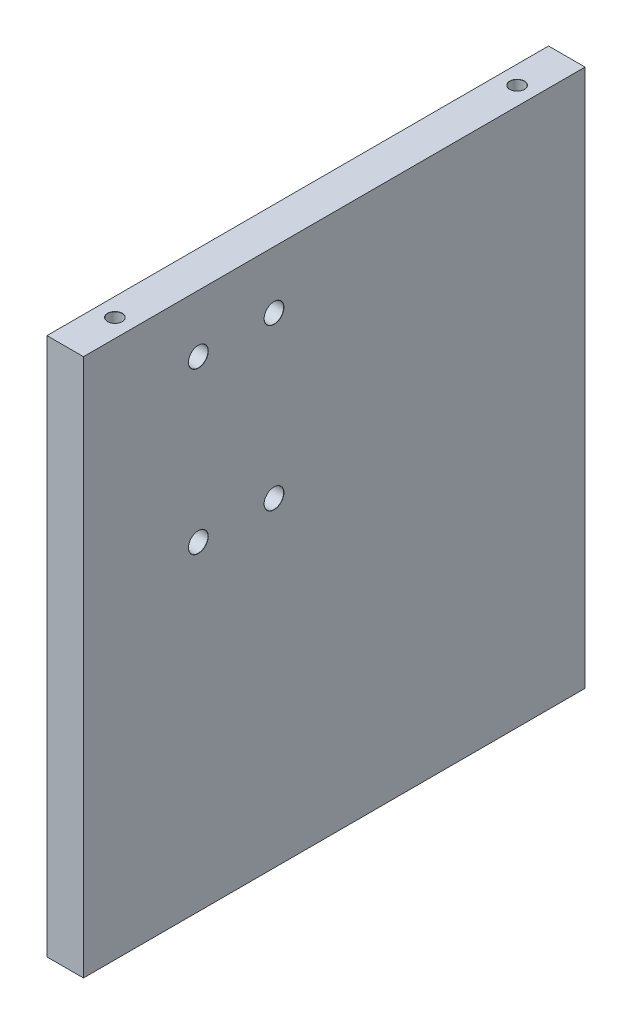
SolidWorks part; units mm, degrees
ref_plane "Front Plane" through (0, 0, 0) normal (0, 0, 1) x (1, 0, 0)
ref_plane "Top Plane" through (0, 0, 0) normal (0, 1, 0) x (1, 0, 0)
ref_plane "Right Plane" through (0, 0, 0) normal (1, 0, 0) x (0, 0, -1)
sketch "Sketch1" plane through (0, 0, 0) normal (1, 0, 0) x (0, 0, -1)
  line L1 (-43.65, -46.825) -> (43.65, -46.825)
  line L2 (-43.65, -46.825) -> (-43.65, 46.825)
  line L3 (-43.65, 46.825) -> (43.65, 46.825)
  line L4 (43.65, -46.825) -> (43.65, 46.825)
  line L5 (-43.65, -46.825) -> (43.65, 46.825) construction
  line L6 (-43.65, 46.825) -> (43.65, -46.825) construction
  point P0 (0, 0)
extrude "Boss-Extrude1" add sketch "Sketch1" along normal blind 6.35
sketch "Sketch2" plane through (0, 46.825, 0) normal (0, 1, 0) x (1, 0, 0)
  line L0 (3.175, 43.65) -> (3.175, 35)
  line L1 (6.35, 43.65) -> (0, 43.65) construction
  line L2 (3.175, -43.65) -> (3.175, -35)
  line L3 (6.35, -43.65) -> (0, -43.65) construction
hole_wizard "Tap Drill for M3x0.5 Tap1" positions "Sketch3" profile "Sketch4" hole size "M3x0.5" standard "ANSI Metric"
sketch "Sketch3" plane through (0, 46.825, 0) normal (0, 1, 0) x (1, 0, 0)
  point P0 (3.175, 35)
  point P3 (3.175, -35)
sketch "Sketch4" plane through (3.175, 46.825, -35) normal (1, 0, 0) x (0, 0, 1)
  line L0 (0, 0) -> (0, 10.7511)
  line L1 (0, 10.7511) -> (1.25, 10)
  line L2 (1.25, 10) -> (1.25, 0.025)
  line L3 (1.25, 0.025) -> (1.275, 0)
  line L5 (1.275, 0) -> (0, 0)
  line L6 (-1.25, 0.025) -> (-1.275, 0) construction
  line L10 (0, 10.7511) -> (-1.25, 10) construction
  line L11 (0, -6.35) -> (0, 107.95) construction
  dimension "Hole Dia." = 2.5
  dimension "Hole Depth" = 10
  dimension "Near C'Sink Dia." = 2.55
  dimension "Near C'Sink Angle" = 90
  dimension "Drill Angle" = 118
sketch "Sketch5" plane through (0, -46.825, 0) normal (0, -1, 0) x (1, 0, 0)
  line L0 (3.175, 43.65) -> (3.175, 35)
  line L1 (3.175, -43.65) -> (3.175, -35)
  line L2 (6.35, -43.65) -> (0, -43.65) construction
hole_wizard "Tap Drill for M3x0.5 Tap2" positions "Sketch6" profile "Sketch7" hole size "M3x0.5" standard "ANSI Metric"
sketch "Sketch6" plane through (0, -46.825, 0) normal (0, -1, 0) x (-1, 0, 0)
  point P0 (-3.175, -35)
  point P3 (-3.175, 35)
sketch "Sketch7" plane through (3.175, -46.825, 35) normal (1, 0, 0) x (0, 0, -1)
  line L0 (0, 0) -> (0, 10)
  line L1 (0, 10) -> (1.25, 9.2489)
  line L2 (1.25, 9.2489) -> (1.25, 0.025)
  line L3 (1.25, 0.025) -> (1.275, 0)
  line L5 (1.275, 0) -> (0, 0)
  line L6 (-1.25, 0.025) -> (-1.275, 0) construction
  line L10 (0, 10) -> (-1.25, 9.2489) construction
  line L11 (0, -6.35) -> (0, 107.95) construction
  dimension "Hole Dia." = 2.5
  dimension "Hole Depth" = 10
  dimension "Near C'Sink Dia." = 2.55
  dimension "Near C'Sink Angle" = 90
  dimension "Drill Angle" = 118
sketch "Sketch11" plane through (6.35, 0, 0) normal (1, 0, 0) x (0, 0, -1)
  line L0 (-43.65, 46.825) -> (-43.65, 36.825)
  line L1 (-43.65, 46.825) -> (-43.65, -46.825) construction
  line L2 (-43.65, 36.825) -> (-23.65, 36.825)
  line L3 (-23.65, 36.825) -> (-23.65, 8.885)
  line L4 (-23.65, 8.885) -> (-10.48, 8.885)
  line L5 (-10.48, 8.885) -> (-10.48, 36.825)
hole_wizard "M3 Clearance Hole2" positions "Sketch12" profile "Sketch13" hole size "M3" standard "ANSI Metric" end condition through all
sketch "Sketch12" plane through (6.35, 0, 0) normal (1, 0, 0) x (0, 0, -1)
  point P0 (-23.65, 36.825)
  point P3 (-10.48, 36.825)
  point P6 (-10.48, 8.885)
  point P9 (-23.65, 8.885)
sketch "Sketch13" plane through (6.35, 36.825, 23.65) normal (0, 1, 0) x (0, 0, -1)
  line L0 (0, 0) -> (0, 6.35)
  line L1 (0, 6.35) -> (1.7, 6.35)
  line L2 (1.7, 6.35) -> (1.7, 0.025)
  line L3 (1.7, 0.025) -> (1.725, 0)
  line L5 (1.725, 0) -> (0, 0)
  line L6 (-1.7, 0.025) -> (-1.725, 0) construction
  line L11 (0, -6.35) -> (0, 107.95) construction
  dimension "Thru Hole Dia." = 3.4
  dimension "Thru Hole Depth" = 6.35
  dimension "Near C'Sink Dia." = 3.45
  dimension "Near C'Sink Angle" = 90
